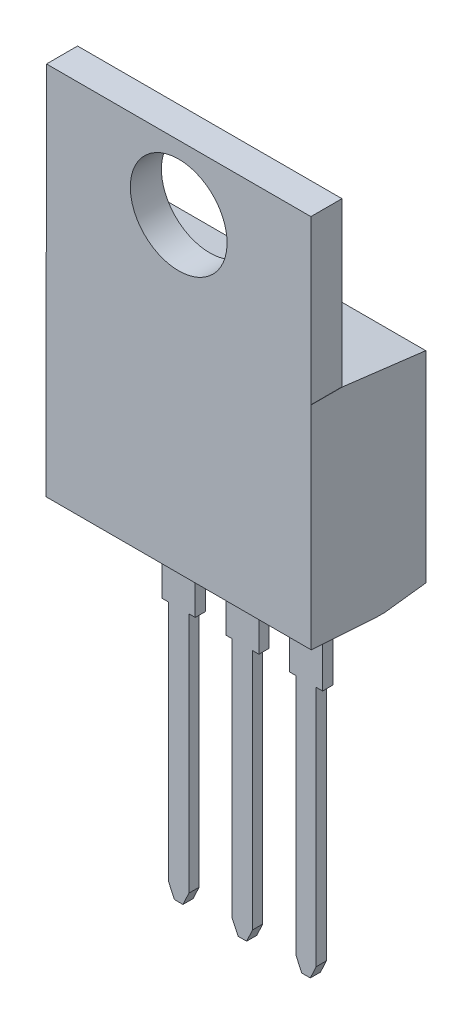
SolidWorks part; units mm, degrees
ref_plane "Vorderansicht" through (0, 0, 0) normal (0, 0, 1) x (1, 0, 0)
ref_plane "Draufsicht" through (0, 0, 0) normal (0, 1, 0) x (1, 0, 0)
ref_plane "Seitenansicht" through (0, 0, 0) normal (1, 0, 0) x (0, 0, -1)
sketch "Skizze1" plane through (0, 0, 0) normal (1, 0, 0) x (0, 0, -1)
  line L0 (0, 0) -> (1.22, 0)
  line L1 (4.4999, -14.7036) -> (2.9, -14.9)
  line L2 (0, -14.7252) -> (0, 0)
  line L3 (1.22, 0) -> (1.22, -6.4)
  line L4 (4.4999, -14.7036) -> (4.4999, -6.8027)
  line L5 (1.22, -6.4) -> (4.4999, -6.8027)
  line L6 (2.9, -14.9) -> (2.5, -14.9)
  line L7 (2.5, -14.9) -> (0, -14.7252)
  dimension "D1" = 1.22
  dimension "D2" = 4.5
  dimension "D3" = 8.5
  dimension "D4" = 83
  dimension "D5" = 6.4
  dimension "D6" = 7
  dimension "D7" = 2.5
  dimension "D8" = 0.4
  dimension "D9" = 4
extrude "Linear austragen1" add sketch "Skizze1" along normal mid plane 10.4
hole_wizard "Ø3.8 (3.8) Durchmesser Bohrung1" positions "Skizze3" profile "Skizze2" hole size "Ø3.8" standard "ISO"
sketch "Skizze3" plane through (0, 0, -1.22) normal (0, 0, -1) x (-1, 0, 0)
  line L0 (-5.2, 0) -> (5.2, 0) construction
  point P0 (0, -2.54)
  dimension "D1" = 2.54
sketch "Skizze2" plane through (0, -2.54, -1.22) normal (1, 0, 0) x (0, 1, 0)
  line L0 (0, 0) -> (0, 6.1416)
  line L1 (0, 6.1416) -> (1.9, 5)
  line L2 (1.9, 5) -> (1.9, 0)
  line L5 (1.9, 0) -> (0, 0)
  line L10 (0, 6.1416) -> (-1.9, 5) construction
  line L11 (0, -6.35) -> (0, 107.95) construction
  dimension "Bohrerdurchmesser" = 3.8
  dimension "Bohrungstiefe" = 5
  dimension "Spitzenwinkel" = 118
sketch "Skizze4" plane through (0, -14.9, 0) normal (0, -1, 0) x (1, 0, 0)
  line L0 (5.2, -2.5) -> (-5.2, -2.5) construction
  line L1 (-3.15, -2.5) -> (-1.85, -2.5)
  line L2 (-3.15, -2.5) -> (-3.15, -2.9)
  line L3 (-3.15, -2.9) -> (-1.85, -2.9)
  line L4 (-1.85, -2.5) -> (-1.85, -2.9)
  line L5 (5.2, -2.9) -> (-5.2, -2.9) construction
  line L6 (0, 0) -> (0, -4.3387) construction
  line L7 (-2.5, -2.5) -> (-2.5, -2.9) construction
  line L8 (-0.65, -2.5) -> (0.65, -2.5)
  line L9 (-0.65, -2.5) -> (-0.65, -2.9)
  line L10 (-0.65, -2.9) -> (0.65, -2.9)
  line L11 (0.65, -2.5) -> (0.65, -2.9)
  line L12 (1.85, -2.5) -> (3.15, -2.5)
  line L13 (1.85, -2.5) -> (1.85, -2.9)
  line L14 (1.85, -2.9) -> (3.15, -2.9)
  line L15 (3.15, -2.5) -> (3.15, -2.9)
  line L16 (2.5, -2.5) -> (2.5, -2.9) construction
  dimension "D1" = 1.3
  dimension "D2" = 1.3
  dimension "D3" = 1.3
  dimension "D4" = 2.5
  dimension "D5" = 2.5
extrude "Linear austragen2" add sketch "Skizze4" along normal blind 3.5
sketch "Skizze5" plane through (0, -18.4, 0) normal (0, -1, 0) x (1, 0, 0)
  line L0 (3.15, -2.5) -> (1.85, -2.5) construction
  line L1 (2.1, -2.5) -> (2.9, -2.5)
  line L2 (2.1, -2.5) -> (2.1, -2.9)
  line L3 (2.1, -2.9) -> (2.9, -2.9)
  line L4 (2.9, -2.5) -> (2.9, -2.9)
  line L5 (1.85, -2.9) -> (3.15, -2.9) construction
  line L6 (0.65, -2.5) -> (-0.65, -2.5) construction
  line L7 (-0.4, -2.5) -> (0.4, -2.5)
  line L8 (-0.4, -2.5) -> (-0.4, -2.9)
  line L9 (-0.4, -2.9) -> (0.4, -2.9)
  line L10 (0.4, -2.5) -> (0.4, -2.9)
  line L11 (-0.65, -2.9) -> (0.65, -2.9) construction
  line L12 (-1.85, -2.5) -> (-3.15, -2.5) construction
  line L13 (-2.9, -2.5) -> (-2.1, -2.5)
  line L14 (-2.9, -2.5) -> (-2.9, -2.9)
  line L15 (-2.9, -2.9) -> (-2.1, -2.9)
  line L16 (-2.1, -2.5) -> (-2.1, -2.9)
  line L17 (-3.15, -2.9) -> (-1.85, -2.9) construction
  line L18 (2.5, -2.5) -> (2.5, -2.9) construction
  line L19 (3.15, -2.5) -> (1.85, -2.5) construction
  line L20 (1.85, -2.9) -> (3.15, -2.9) construction
  line L21 (0, -2.5) -> (0, -2.9) construction
  line L22 (-2.5, -2.5) -> (-2.5, -2.9) construction
  line L23 (-1.85, -2.5) -> (-3.15, -2.5) construction
  line L24 (-3.15, -2.9) -> (-1.85, -2.9) construction
  line L25 (-2.5, -2.5) -> (-2.5, -2.9) construction
  line L26 (0, -2.5) -> (0, -2.9) construction
  line L27 (2.5, -2.5) -> (2.5, -2.9) construction
  dimension "D1" = 0.8
  dimension "D2" = 0.8
  dimension "D3" = 0.8
extrude "Linear austragen3" add sketch "Skizze5" along normal blind 10
chamfer "Fase1" distance 0.5 angle 25 6 edges at (-2.9, -28.4, -2.7) (-2.1, -28.4, -2.7) (0.4, -28.4, -2.7) (-0.4, -28.4, -2.7) (2.1, -28.4, -2.7) (2.9, -28.4, -2.7)
sketch "Skizze7" plane through (-5.2, 0, 0) normal (-1, 0, 0) x (0, 0, 1)
  line L0 (0, 0) -> (0, -14.7252) construction
  line L1 (-1.22, 0) -> (0, 0)
  line L2 (-1.22, 0) -> (-1.22, -6.4)
  line L3 (-1.22, -6.4) -> (0, -6.4)
  line L4 (0, 0) -> (0, -6.4)
extrude "Schnitt-Linear austragen1" cut sketch "Skizze7" against normal blind 0.01
mirror "Spiegeln1" about plane through (0, 0, 0) normal (1, 0, 0) of "Schnitt-Linear austragen1"
